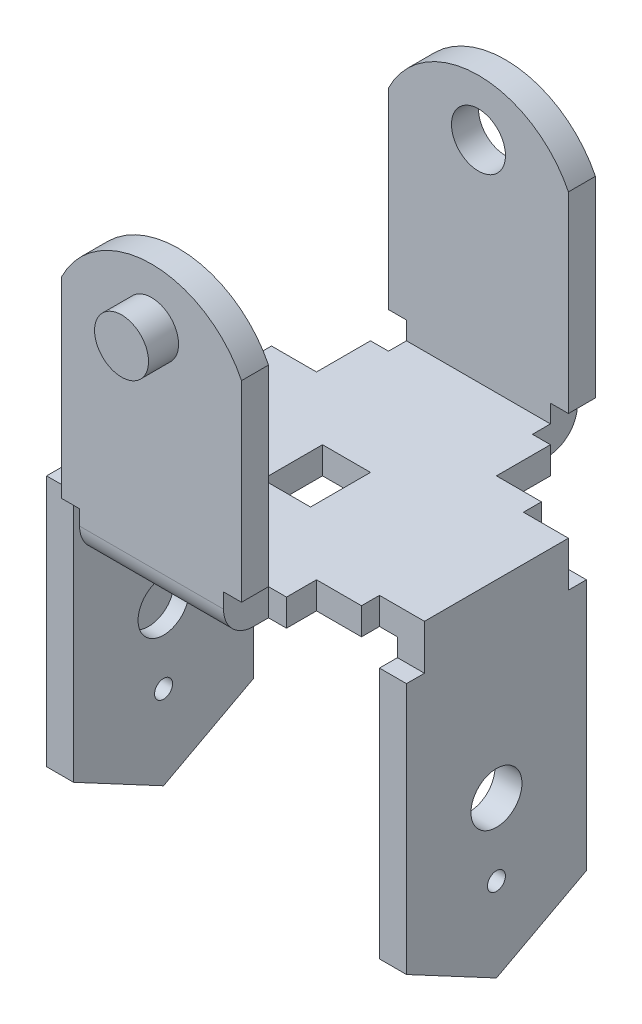
SolidWorks part; units mm, degrees
ref_plane "Front Plane" through (0, 0, 0) normal (0, 0, 1) x (1, 0, 0)
ref_plane "Top Plane" through (0, 0, 0) normal (0, 1, 0) x (1, 0, 0)
ref_plane "Right Plane" through (0, 0, 0) normal (1, 0, 0) x (0, 0, -1)
sketch "Sketch1" plane through (0, 0, 0) normal (0, 0, 1) x (1, 0, 0)
  line L9 (-15, 17.5) -> (-15, -14.5)
  line L12 (-12, -17.5) -> (12, -17.5)
  line L13 (15, 17.5) -> (15, -14.5)
  line L14 (-15, 17.5) -> (15, -17.5) construction
  line L15 (-15, -17.5) -> (15, 17.5) construction
  line L16 (-15, -14.5) -> (-12, -14.5)
  line L17 (-12, -14.5) -> (-12, -17.5)
  line L18 (0, 0) -> (0, -17.5) construction
  line L19 (0, -24.9454) -> (0, 24.9454) construction
  line L20 (12, -14.5) -> (12, -17.5)
  line L21 (15, -14.5) -> (12, -14.5)
  arc A2 (-15, 17.5) -> (15, 17.5) centre (0, 10.1318) cw
  circle A3 centre (0, 17.5) radius 4.5
  point P0 (0, 0)
  point P1 (0, 0)
  dimension "D1" = 35
  dimension "D2" = 30
ref_plane "Plane1" through (0, -17.5, 0) normal (0, 1, 0) x (1, 0, 0)
sketch "Sketch2" plane through (0, -17.5, 0) normal (0, 1, 0) x (1, 0, 0)
  line L11 (-12, 4.5) -> (12, 4.5)
  line L14 (-12, -54.5) -> (12, -54.5)
  line L25 (0, 0) -> (0, -27.0007) construction
  line L26 (-30, -15.0007) -> (-30, -39.0007)
  line L27 (-15, -3) -> (-15, -12.0007)
  line L29 (15, -47.0014) -> (15, -42.0007)
  line L31 (-12, 0) -> (-12, -3)
  line L32 (-12, -3) -> (-15, -3)
  line L33 (15, -12.0007) -> (22.5, -12.0007)
  line L34 (12, -3) -> (15, -3)
  line L35 (12, 0) -> (12, -3)
  line L36 (-12, 0) -> (-12, 4.5)
  line L37 (-12, 4.5) -> (12, 4.5)
  line L38 (12, 4.5) -> (12, 0)
  line L39 (30, -15.0007) -> (30, -39.0007)
  line L40 (-15, -47) -> (-12, -47)
  line L41 (-12, -47) -> (-12, -50)
  line L43 (15, -47.0014) -> (12, -47.0014)
  line L44 (12, -47.0014) -> (12, -50)
  line L45 (-12, -50) -> (-12, -54.5)
  line L46 (-12, -54.5) -> (12, -54.5)
  line L47 (12, -54.5) -> (12, -50)
  line L48 (22.5, -42.0007) -> (15, -42.0007)
  line L49 (15, -12.0007) -> (15, -3)
  line L50 (-22.5, -42.0007) -> (-15, -42.0007)
  line L51 (-15, -12.0007) -> (-22.5, -12.0007)
  line L52 (-15, -42.0007) -> (-15, -47)
  line L53 (0, -32.0007) -> (0, -54.5) construction
  line L55 (30, -39.0007) -> (25.5, -39.0007)
  line L56 (30, -15.0007) -> (25.5, -15.0007)
  line L57 (-30, -39.0007) -> (-25.5, -39.0007)
  line L58 (-30, -15.0007) -> (-25.5, -15.0007)
  line L59 (-25.5, -15.0007) -> (-25.5, -39.0007) construction
  line L62 (22.5, -42.0007) -> (15, -42.0007)
  line L63 (-25.5, -39.0007) -> (-22.5, -39.0007)
  line L64 (-4, -22.0007) -> (4, -22.0007)
  line L65 (-4, -22.0007) -> (-4, -32.0007)
  line L66 (-4, -32.0007) -> (4, -32.0007)
  line L67 (4, -22.0007) -> (4, -32.0007)
  line L68 (-22.5, -39.0007) -> (-22.5, -42.0007)
  line L70 (-25.5, -15.0007) -> (-22.5, -15.0007)
  line L71 (-22.5, -15.0007) -> (-22.5, -12.0007)
  line L72 (15, -12.0007) -> (22.5, -12.0007)
  line L73 (22.5, -15.0007) -> (22.5, -12.0007)
  line L74 (22.5, -39.0007) -> (22.5, -42.0007)
  line L76 (25.5, -39.0007) -> (22.5, -39.0007)
  line L77 (25.5, -15.0007) -> (22.5, -15.0007)
  line L80 (25.5, -15.0007) -> (25.5, -39.0007) construction
  line L81 (30, -15.0007) -> (30, -39.0007)
  point P6 (0, -27.0007)
  dimension "D1" = 24
  dimension "D2" = 10
  dimension "D3" = 8
  dimension "D4" = 4.5
  dimension "D5" = 3
  dimension "D6" = 7.5
  dimension "D7" = 3
ref_plane "Plane2" through (0, 0, 50) normal (0, 0, 1) x (1, 0, 0)
sketch "Sketch3" plane through (0, 0, 50) normal (0, 0, 1) x (1, 0, 0)
  line L8 (-15, 17.5) -> (-15, -14.5)
  line L9 (-15, -14.5) -> (-12, -14.5)
  line L10 (-12, -14.5) -> (-12, -17.5)
  line L11 (-12, -17.5) -> (12, -17.5)
  line L12 (12, -17.5) -> (12, -14.5)
  line L13 (12, -14.5) -> (15, -14.5)
  line L14 (15, -14.5) -> (15, 17.5)
  arc A2 (-15, 17.5) -> (15, 17.5) centre (0, 10.1318) cw
  circle A3 centre (0, 17.5) radius 4.5
ref_plane "Plane3" through (30, 0, 0) normal (1, 0, 0) x (0, 0, -1)
sketch "Sketch4" plane through (30, 0, 0) normal (1, 0, 0) x (0, 0, -1)
  line L6 (-15.0007, -22) -> (-15.0007, -25)
  line L7 (-15.0007, -25) -> (-12.0007, -25)
  line L8 (-12.0007, -25) -> (-12.0007, -60)
  line L11 (-42.0007, -25) -> (-39.0007, -25)
  line L12 (-39.0007, -25) -> (-39.0007, -22)
  line L13 (-39.0007, -25) -> (-39.0007, -22)
  line L14 (-39.0007, -22) -> (-15.0007, -22)
  line L15 (-15.0007, -22) -> (-15.0007, -25)
  line L16 (-42.0007, -25) -> (-42.0007, -60)
  line L19 (-27.0007, -70) -> (-12.0007, -60)
  line L20 (-42.0007, -60) -> (-27.0007, -70)
  circle A0 centre (-27.0007, -42.5) radius 3.3534
  circle A1 centre (-27.0007, -55.625) radius 1.5
  dimension "D1" = 35
ref_plane "Plane4" through (-30, 0, 0) normal (1, 0, 0) x (0, 0, -1)
sketch "Sketch5" plane through (-30, 0, 0) normal (1, 0, 0) x (0, 0, -1)
  line L0 (-39.0007, -22) -> (-39.0007, -25)
  line L1 (-39.0007, -25) -> (-42.0007, -25)
  line L2 (-42.0007, -25) -> (-42.0007, -60)
  line L3 (-42.0007, -60) -> (-27.0007, -70)
  line L4 (-27.0007, -70) -> (-12.0007, -60)
  line L5 (-12.0007, -60) -> (-12.0007, -25)
  line L6 (-12.0007, -25) -> (-15.0007, -25)
  line L7 (-15.0007, -25) -> (-15.0007, -22)
  line L8 (-15.0007, -22) -> (-39.0007, -22)
  circle A0 centre (-27.0007, -42.5) radius 3.3534
  circle A1 centre (-27.0007, -55.625) radius 1.5
extrude "Boss-Extrude1" add sketch "Sketch1" against normal blind 4.5
extrude "Boss-Extrude2" add sketch "Sketch2" against normal blind 4.5
extrude "Boss-Extrude3" add sketch "Sketch3" along normal blind 4.5
fillet "Fillet3" radius 5 1 edges at (0, -22, 54.5)
fillet "Fillet4" radius 5 1 edges at (0, -22, -4.5)
ref_plane "Plane5" through (-25.5, 0, 0) normal (1, 0, 0) x (0, 0, -1)
ref_plane "Plane6" through (25.5, 0, 0) normal (1, 0, 0) x (0, 0, -1)
sketch "Sketch6" plane through (-25.5, 0, 0) normal (1, 0, 0) x (0, 0, -1)
  line L0 (-15.0007, -22) -> (-39.0007, -22)
  line L1 (-39.0007, -22) -> (-39.0007, -25)
  line L2 (-39.0007, -25) -> (-39.0007, -22) construction
  line L3 (-39.0007, -25) -> (-42.0007, -25)
  line L4 (-42.0007, -25) -> (-42.0007, -67)
  line L5 (-42.0007, -25) -> (-42.0007, -60) construction
  line L7 (-12.0007, -67) -> (-12.0007, -25)
  line L8 (-12.0007, -25) -> (-15.0007, -25)
  line L9 (-15.0007, -25) -> (-15.0007, -22)
  line L11 (-27.0007, -75) -> (-42.0007, -67)
  line L12 (-27.0007, -75) -> (-12.0007, -67)
  circle A0 centre (-27.0007, -49) radius 4.25
  circle A1 centre (-27.0007, -61) radius 1.5
  dimension "D2" = 12
extrude "Boss-Extrude4" add sketch "Sketch6" against normal blind 4.5
sketch "Sketch7" plane through (25.5, 0, 0) normal (1, 0, 0) x (0, 0, -1)
  line L0 (-39.0007, -22) -> (-39.0007, -25)
  line L1 (-39.0007, -25) -> (-42.0007, -25)
  line L2 (-42.0007, -25) -> (-42.0007, -67)
  line L3 (-42.0007, -67) -> (-27.0007, -75)
  line L4 (-27.0007, -75) -> (-12.0007, -67)
  line L5 (-12.0007, -67) -> (-12.0007, -25)
  line L6 (-12.0007, -25) -> (-15.0007, -25)
  line L7 (-15.0007, -25) -> (-15.0007, -22)
  line L8 (-15.0007, -22) -> (-39.0007, -22)
  circle A0 centre (-27.0007, -49) radius 4.25
  circle A1 centre (-27.0007, -61) radius 1.5
extrude "Boss-Extrude5" add sketch "Sketch7" along normal blind 4.5
sketch "Sketch8" plane through (-30, 0, 0) normal (-1, 0, 0) x (0, 0, 1)
  circle A0 centre (27.0007, -49) radius 4.25
extrude "Boss-Extrude6" add sketch "Sketch8" against normal blind 2
sketch "Sketch9" plane through (0, 0, 50) normal (0, 0, -1) x (-1, 0, 0)
  line L0 (4.5, 17.5) -> (0, 17.5)
  circle A0 centre (0, 17.5) radius 4.5 construction
  circle A1 centre (0, 17.5) radius 4.5
extrude "Boss-Extrude7" add sketch "Sketch9" against normal blind 9.5
sketch "Sketch10" plane through (-25.5, 0, 0) normal (1, 0, 0) x (0, 0, -1)
  circle A0 centre (-27.0007, -49) radius 4.25
